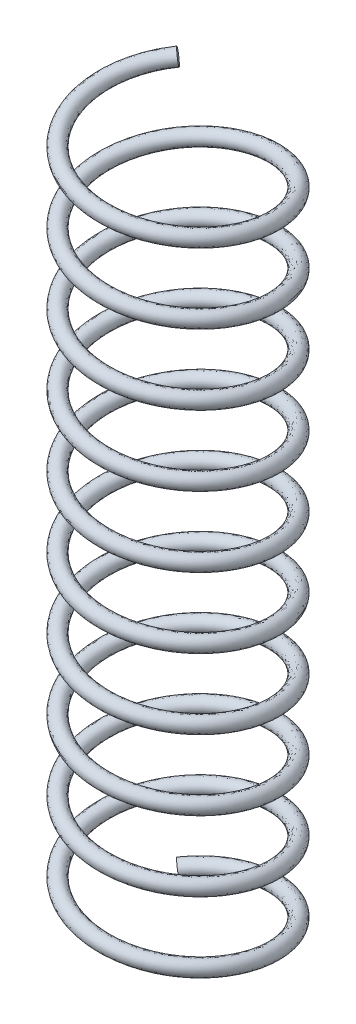
SolidWorks part; units mm, degrees
ref_plane "Front Plane" through (0, 0, 0) normal (0, 0, 1) x (1, 0, 0)
ref_plane "Top Plane" through (0, 0, 0) normal (0, 1, 0) x (1, 0, 0)
ref_plane "Right Plane" through (0, 0, 0) normal (1, 0, 0) x (0, 0, -1)
sketch "Sketch1" plane through (0, 0, 0) normal (0, 1, 0) x (1, 0, 0)
  circle A0 centre (0, 0) radius 8.5
  dimension "D1" = 17
curve "Helix/Spiral1" pitch 7 height 70 turns 10
ref_plane "Plane1" through (-6.0104, 0, -6.0104) normal (0.7011, 0.13, -0.7011) x (-0.7131, 0.1278, -0.6894)
sweep "Sweep1" add path "Helix/Spiral1" circular profile diameter 1.5 parameters "D3"=1.5
